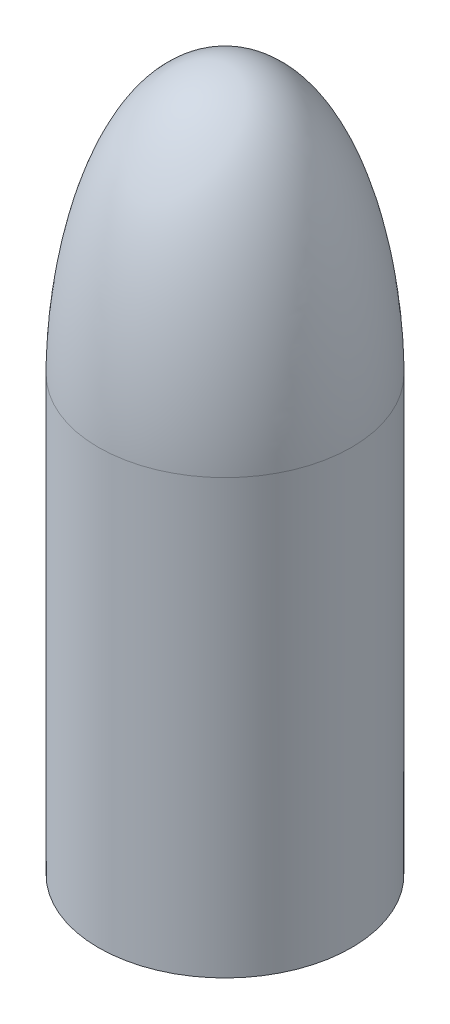
SolidWorks part; units mm, degrees
ref_plane "Front Plane" through (0, 0, 0) normal (0, 0, 1) x (1, 0, 0)
ref_plane "Top Plane" through (0, 0, 0) normal (0, 1, 0) x (1, 0, 0)
ref_plane "Right Plane" through (0, 0, 0) normal (1, 0, 0) x (0, 0, -1)
sketch "Sketch1" plane through (0, 0, 0) normal (0, 1, 0) x (1, 0, 0)
  circle A0 centre (0, 0) radius 35
  circle A1 centre (0, 0) radius 36.5
  dimension "D1" = 70
  dimension "D2" = 1.5
extrude "Boss-Extrude1" add sketch "Sketch1" along normal blind 125
sketch "Sketch2" plane through (0, 0, 0) normal (0, 0, 1) x (1, 0, 0)
  line L0 (0, 125) -> (0, 204.6854) construction
  line L1 (36.5, 125) -> (-36.5, 125) construction
  line L2 (-35, 158.3922) -> (-35, 91.6078) construction
  line L3 (26.0425, 200.7892) -> (-26.0425, 200.7892) construction
  line L4 (-35, 125) -> (-36.5, 125)
  line L5 (0, 200.7892) -> (0, 202.2892)
  spline S0 degree 3 poles (-35, 125) (-35, 156.1922) (-24.5408, 200.7892) (0, 200.7892) knots 0 0 0 0 1 1 1 1
  spline S1 degree 1 poles (-36.5, 125) (0, 202.2892) knots 0 0 1 1 construction
  spline S2 degree 3 poles (-36.5, 125) (-36.5, 125.9976) (-36.4794, 127.9759) (-36.3547, 132.0663) (-36.0409, 137.3058) (-35.4065, 143.7437) (-34.2092, 152.4065) (-32.0392, 163.1802) (-28.3054, 175.3566) (-23.376, 186.1228) (-18.1898, 193.3765) (-13.3125, 197.7966) (-9.2712, 200.3141) (-5.5749, 201.6472) (-2.4507, 202.1956) (-0.8118, 202.2892) (0, 202.2892) knots 0 0 0 0 0.03125 0.0625 0.125 0.1875 0.25 0.375 0.5 0.625 0.75 0.8125 0.875 0.9375 0.96875 1 1 1 1
  dimension "D1" = 1.5
revolve "Revolve1" add sketch "Sketch2" angle 360 about L0
